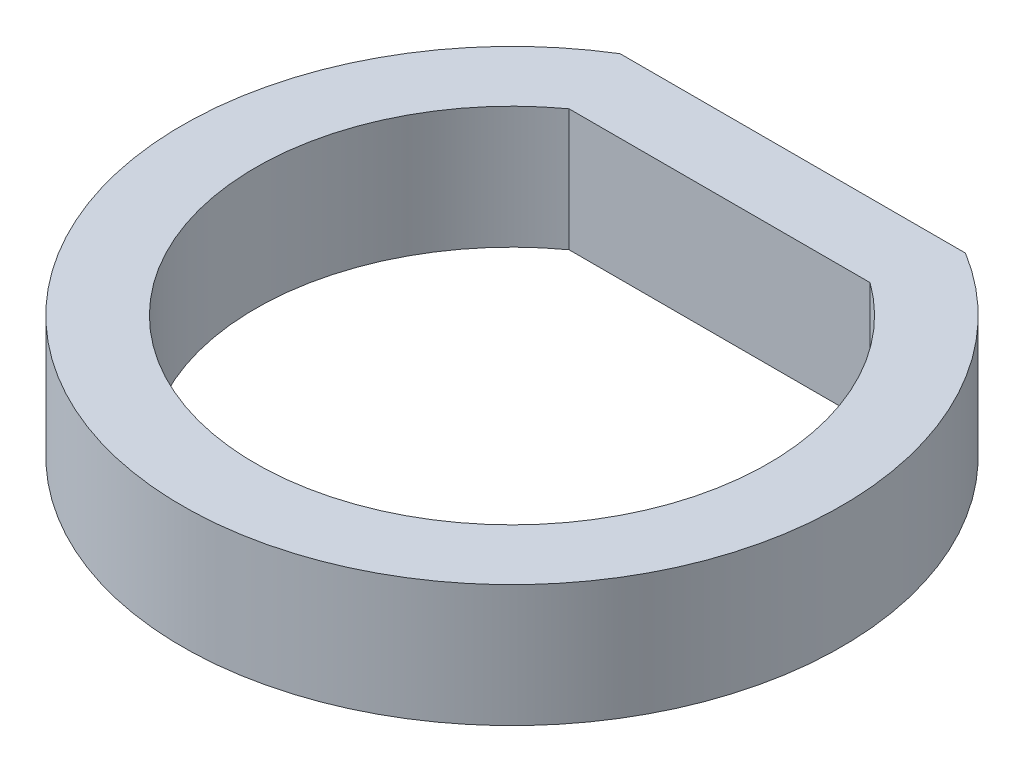
SolidWorks part; units mm, degrees
ref_plane "Plan de face" through (0, 0, 0) normal (0, 0, 1) x (1, 0, 0)
ref_plane "Plan de dessus" through (0, 0, 0) normal (0, 1, 0) x (1, 0, 0)
ref_plane "Plan de droite" through (0, 0, 0) normal (1, 0, 0) x (0, 0, -1)
sketch "Esquisse2" plane through (0, 0, 0) normal (0, 1, 0) x (1, 0, 0)
  line L0 (-18.8448, 31.0643) -> (-6.516, 31.0643)
  line L1 (-19.7515, 34.0643) -> (-5.6093, 34.0643)
  line L2 (-12.6804, 12.0643) -> (2.9236, 12.0643)
  circle A0 centre (-12.6804, 22.5643) radius 10.5
  circle A1 centre (-12.6804, 22.5643) radius 13.5
  dimension "D1" = 21
  dimension "D2" = 27
  dimension "D3" = 3
  dimension "D5" = 3
  dimension "D6" = 19
  dimension "D7" = 19
extrude "Boss.-Extru.2" add sketch "Esquisse2" along normal blind 5
